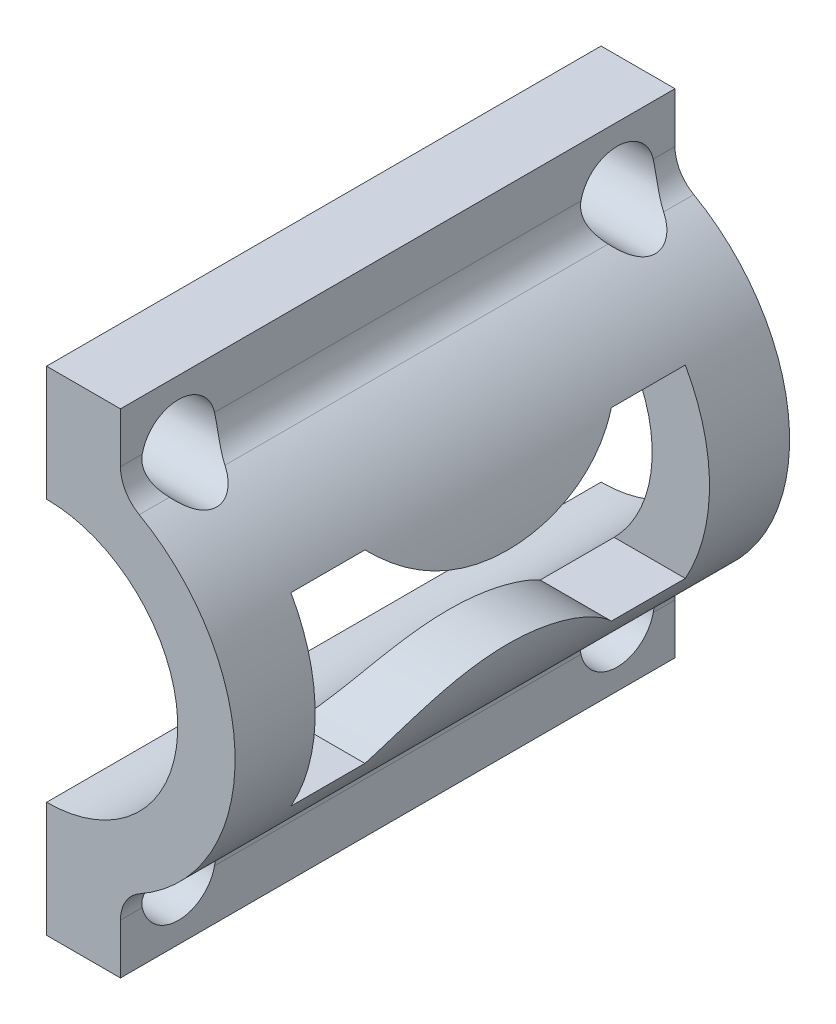
SolidWorks part; units mm, degrees
ref_plane "Front Plane" through (0, 0, 0) normal (0, 0, 1) x (1, 0, 0)
ref_plane "Top Plane" through (0, 0, 0) normal (0, 1, 0) x (1, 0, 0)
ref_plane "Right Plane" through (0, 0, 0) normal (1, 0, 0) x (0, 0, -1)
sketch "Sketch1" plane through (0, 0, 0) normal (0, 0, 1) x (1, 0, 0)
  line L0 (0, 10.65) -> (0, 20)
  line L1 (0, 20) -> (6, 20)
  line L2 (6, 20) -> (6, 14.0744)
  line L3 (-1000, 0) -> (49000, 0) construction
  line L4 (6, -20) -> (6, -14.0744)
  line L5 (0, -20) -> (6, -20)
  line L6 (0, -10.65) -> (0, -20)
  arc A0 (0, -10.65) -> (0, 10.65) centre (0, 0) ccw
  arc A1 (6, -14.0744) -> (6, 14.0744) centre (0, 0) ccw
  dimension "D3" = 40
  dimension "D4" = 15.3
  dimension "D1" = 21.3
  dimension "D2" = 6
extrude "Boss-Extrude2" add sketch "Sketch1" along normal mid plane 45
fillet "Fillet1" radius 3 2 edges at (6, -14.0744, 0) (6, 14.0744, 0)
sketch "Sketch2" plane through (0, 0, 0) normal (-1, 0, 0) x (0, 0, 1)
  line L0 (-22.5, 20) -> (-22.5, 10.65) construction
  line L2 (22.5, 20) -> (-22.5, 20) construction
  line L3 (22.5, -20) -> (-22.5, -20) construction
  line L4 (22.5, -10.65) -> (22.5, -20) construction
  circle A0 centre (-17.8, 15.3) radius 3
  circle A1 centre (17.8, 15.3) radius 3
  circle A2 centre (17.8, -15.3) radius 3
  circle A3 centre (-17.8, -15.3) radius 3
  dimension "D1" = 6
  dimension "D2" = 4.7
  dimension "D3" = 4.7
  dimension "D4" = 4.7
  dimension "D5" = 4.7
extrude "Cut-Extrude1" cut sketch "Sketch2" against normal blind 45
sketch "Sketch3" plane through (0, 0, 0) normal (-1, 0, 0) x (0, 0, 1)
  line L1 (16, 7.5) -> (10, 7.5)
  line L2 (16, 7.5) -> (16, -7.5)
  line L3 (16, -7.5) -> (10, -7.5)
  line L5 (-10, 7.5) -> (-16, 7.5)
  line L7 (-10, -7.5) -> (-16, -7.5)
  line L8 (-16, 7.5) -> (-16, -7.5)
  arc A0 (10, 7.5) -> (-10, 7.5) centre (0, 17.298) cw
  arc A1 (10, -7.5) -> (-10, -7.5) centre (0, -17.298) ccw
  point P8 (-16, 0)
  dimension "D5" = 14
  dimension "D6" = 14
  dimension "D1" = 6
  dimension "D2" = 10
  dimension "D3" = 10
  dimension "D4" = 15
extrude "Cut-Extrude2" cut sketch "Sketch3" against normal through all
